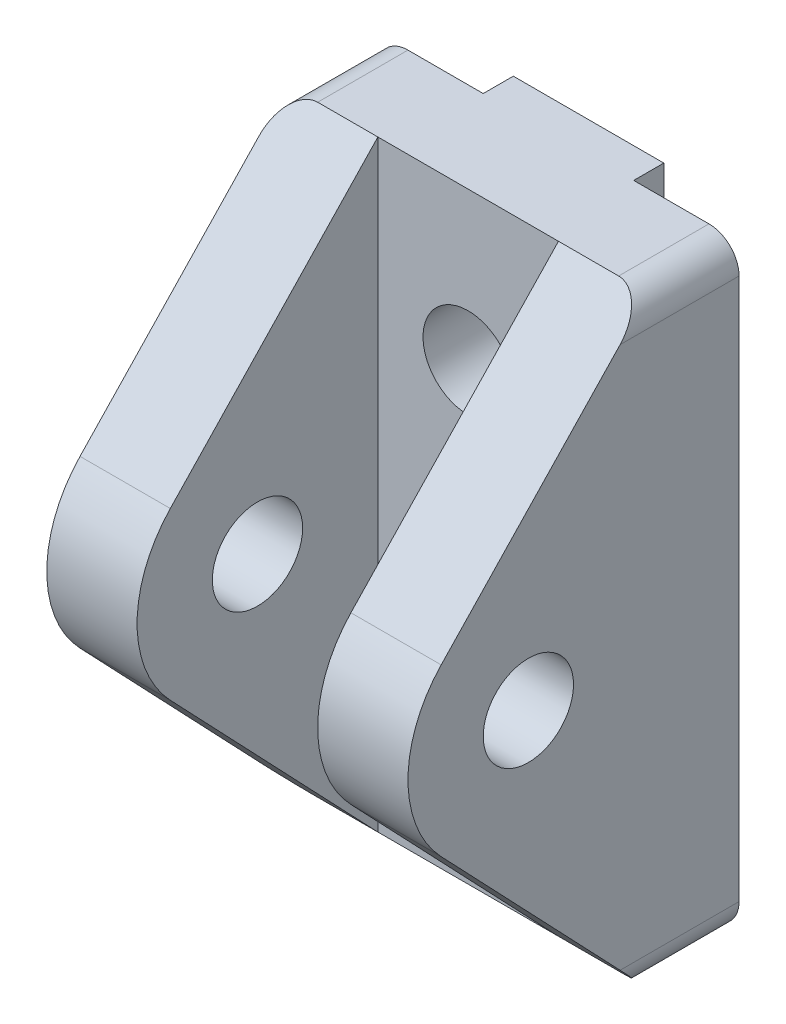
SolidWorks part; units mm, degrees
material "Custom Plastic"
ref_plane "Front Plane" through (0, 0, 0) normal (0, 0, 1) x (1, 0, 0)
ref_plane "Top Plane" through (0, 0, 0) normal (0, 1, 0) x (1, 0, 0)
ref_plane "Right Plane" through (0, 0, 0) normal (1, 0, 0) x (0, 0, -1)
sketch "Sketch1" plane through (0, 0, 0) normal (0, 0, 1) x (1, 0, 0)
  line L0 (0, 5) -> (0, -5) construction
  line L1 (-6, -10) -> (6, -10)
  line L2 (-6, -10) -> (-6, 10)
  line L3 (-6, 10) -> (6, 10)
  line L4 (6, -10) -> (6, 10)
  line L5 (-6, -10) -> (6, 10) construction
  line L6 (-6, 10) -> (6, -10) construction
  circle A0 centre (0, 5) radius 1.5
  circle A1 centre (0, -5) radius 1.5
  point P0 (0, 0)
  point P10 (0, 0)
  dimension "D3" = 3
  dimension "D4" = 3
  dimension "D1" = 12
  dimension "D2" = 20
  dimension "D5" = 10
extrude "Boss-Extrude1" add sketch "Sketch1" along normal blind 3
sketch "Sketch3" plane through (0, 0, 0) normal (0, 0, -1) x (-1, 0, 0)
  line L0 (6, -10) -> (-6, -10) construction
  line L1 (-2.5, -10) -> (2.5, -10)
  line L2 (-2.5, -10) -> (-2.5, -7.4495)
  line L3 (-2.5, 10) -> (2.5, 10)
  line L4 (2.5, -10) -> (2.5, -7.4495)
  line L5 (-6, 10) -> (6, 10) construction
  line L6 (-2.5, 7.4495) -> (-2.5, 10)
  line L7 (2.5, 7.4495) -> (2.5, 10)
  line L8 (2.5, -2.5505) -> (2.5, 2.5505)
  line L9 (-2.5, -2.5505) -> (-2.5, 2.5505)
  arc A5 (-2.5, 2.5505) -> (2.5, 2.5505) centre (0, 5) ccw
  arc A6 (2.5, -2.5505) -> (-2.5, -2.5505) centre (0, -5) ccw
  arc A8 (2.5, 7.4495) -> (-2.5, 7.4495) centre (0, 5) ccw
  arc A9 (-2.5, -7.4495) -> (2.5, -7.4495) centre (0, -5) ccw
  point P8 (0, -10)
  dimension "D2" = 3.5
  dimension "D3" = 3.5
  dimension "D1" = 5
extrude "Boss-Extrude2" add sketch "Sketch3" along normal blind 1
fillet "Fillet1" radius 0.25 8 edges at (2.5, -7.4495, -0.5) (-2.5, -7.4495, -0.5) (-2.5, -2.5505, -0.5) (2.5, -2.5505, -0.5) (2.5, 2.5505, -0.5) (-2.5, 2.5505, -0.5) (-2.5, 7.4495, -0.5) (2.5, 7.4495, -0.5)
sketch "Sketch4" plane through (0, 0, 0) normal (1, 0, 0) x (0, 0, -1)
  line L0 (-3, 10) -> (-9.8966, 2.7586)
  line L1 (-9.8966, -2.7586) -> (-3, -10)
  line L2 (-3, -10) -> (-3, 10)
  arc A0 (-9.8966, 2.7586) -> (-9.8966, -2.7586) centre (-7, 0) ccw
  circle A1 centre (-7, 0) radius 1.5
  point P10 (-11, 0)
  dimension "D1" = 4
  dimension "D2" = 3
  dimension "D3" = 8
extrude "Boss-Extrude3" add sketch "Sketch4" along normal blind 3 from offset 3
mirror "Mirror2" about plane through (0, 0, 0) normal (1, 0, 0) of "Boss-Extrude3"
fillet "Fillet2" radius 1 4 edges at (-6, -10, 1.5) (6, -10, 1.5) (6, 10, 1.5) (-6, 10, 1.5)
